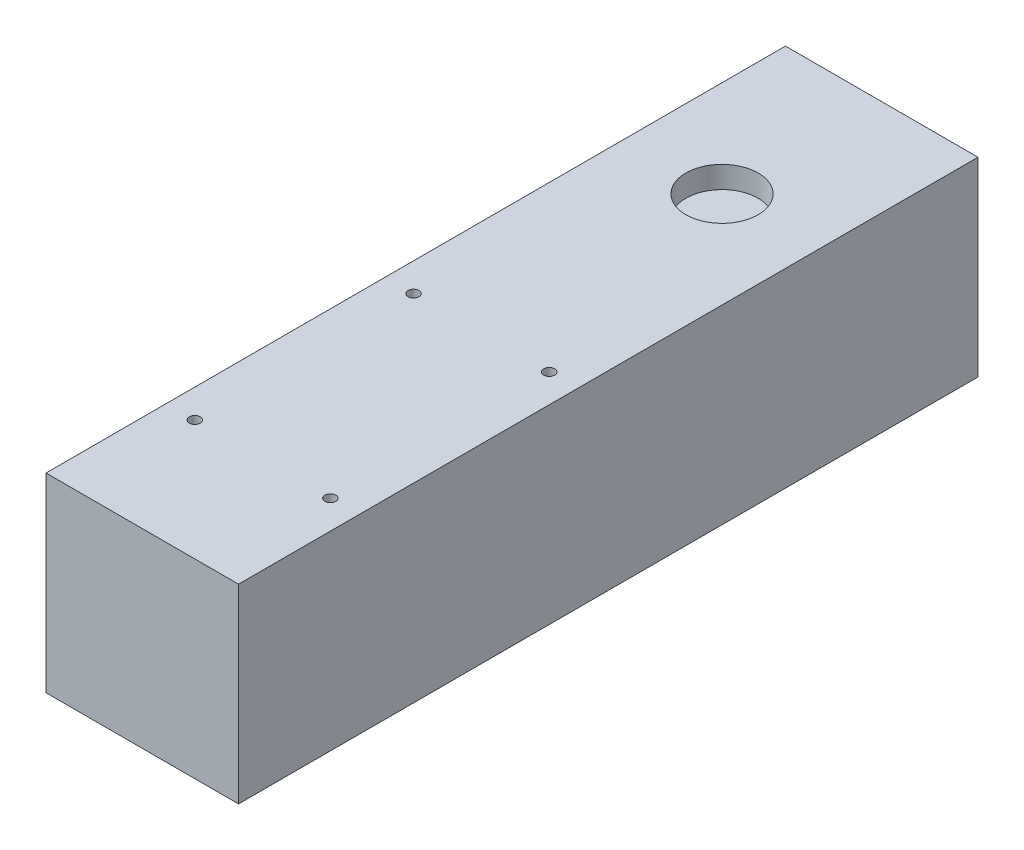
SolidWorks part; units mm, degrees
ref_plane "前视基准面" through (0, 0, 0) normal (0, 0, 1) x (1, 0, 0)
ref_plane "上视基准面" through (0, 0, 0) normal (0, 1, 0) x (1, 0, 0)
ref_plane "右视基准面" through (0, 0, 0) normal (1, 0, 0) x (0, 0, -1)
sketch "草图1" plane through (0, 0, 0) normal (0, 1, 0) x (1, 0, 0)
  line L1 (-44, 169) -> (44, 169)
  line L2 (-44, 169) -> (-44, -169)
  line L3 (-44, -169) -> (44, -169)
  line L4 (44, 169) -> (44, -169)
  line L5 (-44, 169) -> (44, -169) construction
  line L6 (-44, -169) -> (44, 169) construction
  point P0 (0, 0)
  dimension "D1" = 88
  dimension "D2" = 338
extrude "凸台-拉伸1" add sketch "草图1" along normal blind 87
sketch "草图2" plane through (0, 0, 0) normal (0, -1, 0) x (1, 0, 0)
  line L0 (-44, 169) -> (44, 169) construction
  line L1 (44, 169) -> (44, -169) construction
  circle A0 centre (31, 114) radius 2.5
  dimension "D1" = 55
  dimension "D2" = 13
extrude "切除-拉伸1" cut sketch "草图2" against normal through all
pattern_linear "阵列(线性)1" count 2 spacing 100 along (0, 0, -1) count 2 spacing 62 along (-1, 0, 0) of "切除-拉伸1"
sketch "草图3" plane through (0, 87, 0) normal (0, 1, 0) x (1, 0, 0)
  line L0 (-44, -169) -> (44, -169) construction
  circle A0 centre (0, 96) radius 16.5243
  dimension "D1" = 265
extrude "切除-拉伸2" cut sketch "草图3" against normal blind 10
